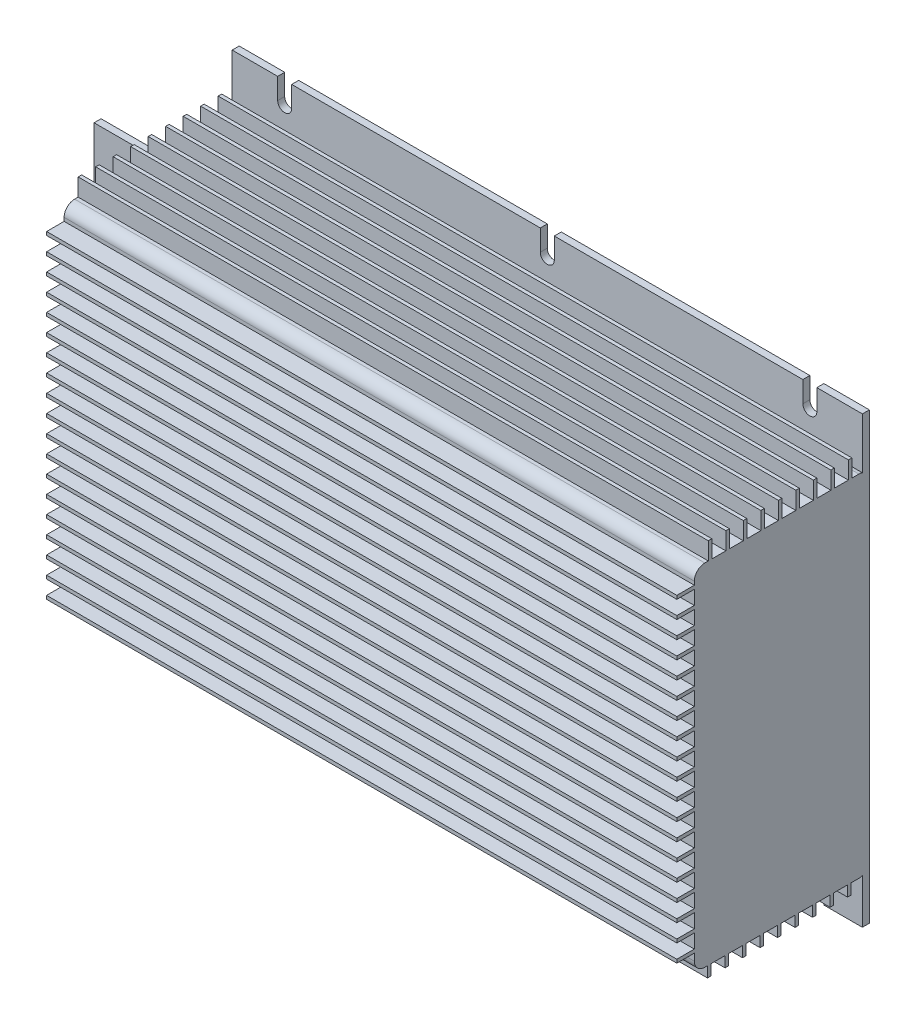
SolidWorks part; units mm, degrees
ref_plane "前视基准面" through (0, 0, 0) normal (0, 0, 1) x (1, 0, 0)
ref_plane "上视基准面" through (0, 0, 0) normal (0, 1, 0) x (1, 0, 0)
ref_plane "右视基准面" through (0, 0, 0) normal (1, 0, 0) x (0, 0, -1)
sketch "草图1" plane through (0, 0, 0) normal (0, 0, 1) x (1, 0, 0)
  line L1 (-84.9269, 43.7787) -> (95.0731, 43.7787)
  line L2 (-84.9269, 43.7787) -> (-84.9269, -56.2213)
  line L3 (-84.9269, -56.2213) -> (95.0731, -56.2213)
  line L4 (95.0731, 43.7787) -> (95.0731, -56.2213)
  dimension "D1" = 180
  dimension "D2" = 100
extrude "凸台-拉伸1" add sketch "草图1" along normal blind 50
fillet "圆角1" radius 3 4 edges at (5.0731, 43.7787, 0) (5.0731, 43.7787, 50) (5.0731, -56.2213, 50) (5.0731, -56.2213, 0)
sketch "草图2" plane through (0, 0, 0) normal (0, 0, -1) x (-1, 0, 0)
  line L0 (-5.0731, 58.1594) -> (-5.0731, -68.8406) construction
  line L1 (-95.0731, 58.1594) -> (84.9269, 58.1594)
  line L2 (-95.0731, 58.1594) -> (-95.0731, -68.8406)
  line L3 (-95.0731, -68.8406) -> (84.9269, -68.8406)
  line L4 (84.9269, 58.1594) -> (84.9269, -68.8406)
  line L5 (-95.0731, -5.3406) -> (84.9269, -5.3406) construction
  line L6 (-5.0731, 40.7787) -> (-5.0731, -51.46) construction
  line L7 (84.9269, 40.7787) -> (-95.0731, 40.7787) construction
  line L8 (-95.0731, -6.2213) -> (84.9269, -6.2213) construction
  line L9 (-95.0731, -53.2213) -> (-95.0731, 40.7787) construction
  line L10 (84.9269, 40.7787) -> (84.9269, -53.2213) construction
  point P18 (-5.0731, -5.3406)
  point P19 (-5.0731, -5.3406)
  dimension "D1" = 180
  dimension "D2" = 127
extrude "凸台-拉伸2" add sketch "草图2" against normal blind 2
sketch "草图3" plane through (0, 0, 50) normal (0, 0, 1) x (1, 0, 0)
  line L0 (-84.9269, 40.7787) -> (-84.9269, -53.2213) construction
  line L1 (-84.9269, 39.7787) -> (95.0731, 39.7787)
  line L2 (-84.9269, 39.7787) -> (-84.9269, 38.7787)
  line L3 (-84.9269, 38.7787) -> (95.0731, 38.7787)
  line L4 (95.0731, 39.7787) -> (95.0731, 38.7787)
  dimension "D1" = 180
  dimension "D2" = 1
  dimension "D3" = 1
extrude "凸台-拉伸3" add sketch "草图3" along normal blind 5
pattern_linear "阵列(线性)1" count 19 spacing 5 along (0, -1, 0) of "凸台-拉伸3"
sketch "草图4" plane through (0, 43.7787, 0) normal (0, 1, 0) x (1, 0, 0)
  line L0 (-84.9269, -47) -> (-84.9269, -3) construction
  line L1 (-84.9269, -45) -> (95.0731, -45)
  line L2 (-84.9269, -45) -> (-84.9269, -46)
  line L3 (-84.9269, -46) -> (95.0731, -46)
  line L4 (95.0731, -45) -> (95.0731, -46)
  dimension "D1" = 180
  dimension "D2" = 1
  dimension "D3" = 1
extrude "凸台-拉伸4" add sketch "草图4" along normal blind 5
sketch "草图5" plane through (-84.9269, 0, 0) normal (-1, 0, 0) x (0, 0, 1)
  line L0 (0, -5.3406) -> (55, -5.2213) construction
  line L1 (0, 58.1594) -> (0, -68.8406) construction
ref_plane "基准面4" through (0, -5.3406, 0.0116) normal (0, -1, 0.0022) x (0, 0.0022, 1)
mirror "镜向1" about plane through (0, -5.3406, 0.0116) normal (0, -1, 0.0022) of "凸台-拉伸4"
pattern_linear "阵列(线性)2" count 9 spacing 5 along (0, 0, -1) of "镜向1", "凸台-拉伸4"
sketch "草图6" plane through (0, 0, 2) normal (0, 0, 1) x (1, 0, 0)
  line L0 (-69.9269, -62.8406) -> (-69.9269, -68.8406)
  line L1 (-69.9269, -68.8406) -> (-65.9269, -68.8406)
  line L2 (95.0731, -68.8406) -> (-84.9269, -68.8406) construction
  line L3 (-65.9269, -62.8406) -> (-65.9269, -68.8406)
  line L4 (-84.9269, 43.6071) -> (-84.9269, 58.1594) construction
  line L6 (-84.9269, 58.1594) -> (95.0731, 58.1594) construction
  line L7 (-71.9269, 52.1594) -> (-71.9269, 58.1594)
  line L8 (-71.9269, 58.1594) -> (-67.9269, 58.1594)
  line L9 (-67.9269, 58.1594) -> (-67.9269, 52.1594)
  arc A0 (-65.9269, -62.8406) -> (-69.9269, -62.8406) centre (-67.9269, -62.8406) ccw
  arc A1 (-71.9269, 52.1594) -> (-67.9269, 52.1594) centre (-69.9269, 52.1594) ccw
  dimension "D1" = 15
  dimension "D3" = 15
  dimension "D2" = 6
  dimension "D4" = 6
extrude "切除-拉伸1" cut sketch "草图6" against normal blind 10
pattern_linear "阵列(线性)3" count 3 spacing 75 along (1, 0, 0) of "切除-拉伸1"
sketch "草图7" plane through (-84.9269, 0, 0) normal (-1, 0, 0) x (0, 0, 1)
  line L0 (16.4518, 4.8992) -> (16.4518, -13.1008)
  line L1 (16.4518, 34.8992) -> (14.4518, 34.8992)
  line L2 (16.4518, 34.8992) -> (16.4518, 16.8992)
  line L3 (16.4518, 16.8992) -> (14.4518, 16.8992)
  line L4 (14.4518, 34.8992) -> (14.4518, 16.8992)
  line L5 (16.4518, 4.8992) -> (14.4518, 4.8992)
  line L6 (14.4518, 4.8992) -> (14.4518, -13.1008)
  line L7 (16.4518, -13.1008) -> (14.4518, -13.1008)
  line L8 (16.4518, -25.1008) -> (16.4518, -43.1008)
  line L9 (16.4518, -25.1008) -> (14.4518, -25.1008)
  line L10 (14.4518, -25.1008) -> (14.4518, -43.1008)
  line L11 (16.4518, -43.1008) -> (14.4518, -43.1008)
  dimension "D1" = 18
  dimension "D2" = 2
  dimension "D3" = 3
extrude "凸台-拉伸5" add sketch "草图7" along normal blind 25
